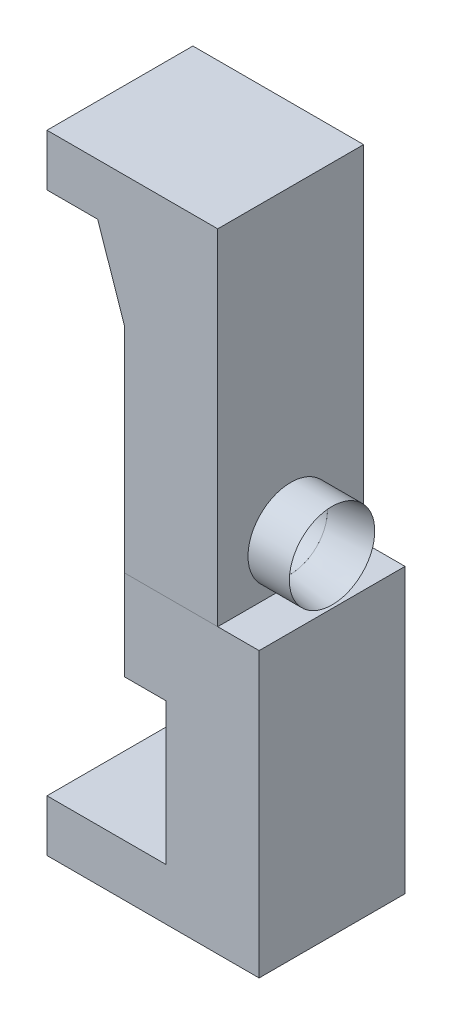
SolidWorks part; units mm, degrees
ref_plane "Front Plane" through (0, 0, 0) normal (0, 0, 1) x (1, 0, 0)
ref_plane "Top Plane" through (0, 0, 0) normal (0, 1, 0) x (1, 0, 0)
ref_plane "Right Plane" through (0, 0, 0) normal (1, 0, 0) x (0, 0, -1)
sketch "Sketch1" plane through (0, 0, 0) normal (0, 0, 1) x (1, 0, 0)
  line L0 (9, 0) -> (9, 3.55)
  line L1 (9, 4.125) -> (13, 4.125)
  line L2 (9, 3.55) -> (13, 4.125)
  line L4 (9, 4.125) -> (9, 3.55)
  line L5 (9, 0) -> (16.8573, 0) construction
  dimension "D2" = 0.575
  dimension "D3" = 4
  dimension "D4" = 9
  dimension "D5" = 3.55
revolve "Revolve1" add sketch "Sketch1" angle 360 about L5
sketch "Sketch2" plane through (0, 0, 0) normal (0, 0, 1) x (1, 0, 0)
  line L0 (0, 0) -> (0, 16.225)
  line L1 (0, 16.225) -> (-2.6, 23.875)
  line L2 (-2.6, 23.875) -> (-7.5, 23.875)
  line L3 (-7.5, 23.875) -> (-7.5, 28.875)
  line L4 (-7.5, 28.875) -> (0, 28.875)
  line L5 (0, 28.875) -> (0, 16.225)
  line L6 (0, 0) -> (-10.3703, 0) construction
  line L7 (0, -13.125) -> (0, -4.425)
  line L8 (0, -13.125) -> (4, -13.125)
  line L9 (4, -13.125) -> (4, -26.825)
  line L10 (4, -26.825) -> (-7.5, -26.825)
  line L11 (-7.5, -31.825) -> (13, -31.825)
  line L12 (13, -31.825) -> (13, -4.425)
  line L13 (-7.5, -31.825) -> (-7.5, -26.825)
  line L14 (0, -4.425) -> (0, 0)
  line L15 (0, -4.425) -> (13, -4.425)
  dimension "D1" = 13.7
  dimension "D2" = 8.7
  dimension "D3" = 4
  dimension "D4" = 5
  dimension "D5" = 20.5
  dimension "D6" = 5
  dimension "D7" = 2.6
  dimension "D8" = 29.35
  dimension "D9" = 7.65
  dimension "D10" = 13
  dimension "D11" = 4.425
extrude "Boss-Extrude1" add sketch "Sketch2" along normal mid plane 14.1 separate body contours L15 L7 L8 L9 L10 L13 L11 L12 | L5 L4 L3 L2 L1
sketch "Sketch3" plane through (0, 0, 0) normal (1, 0, 0) x (0, 0, -1)
  line L1 (-7.05, 28.875) -> (7.05, 28.875)
  line L2 (-7.05, 28.875) -> (-7.05, -4.425)
  line L3 (-7.05, -4.425) -> (7.05, -4.425)
  line L4 (7.05, 28.875) -> (7.05, -4.425)
extrude "Boss-Extrude7" add sketch "Sketch3" along normal blind 9 contours L4 L2 L1 L3 | L4 L2 L3
sketch "Sketch4" plane through (9, 0, 0) normal (1, 0, 0) x (0, 0, -1)
  circle A0 centre (0, 0) radius 3.55
  dimension "D1" = 7.1
extrude "Cut-Extrude1" cut sketch "Sketch4" against normal blind 9
